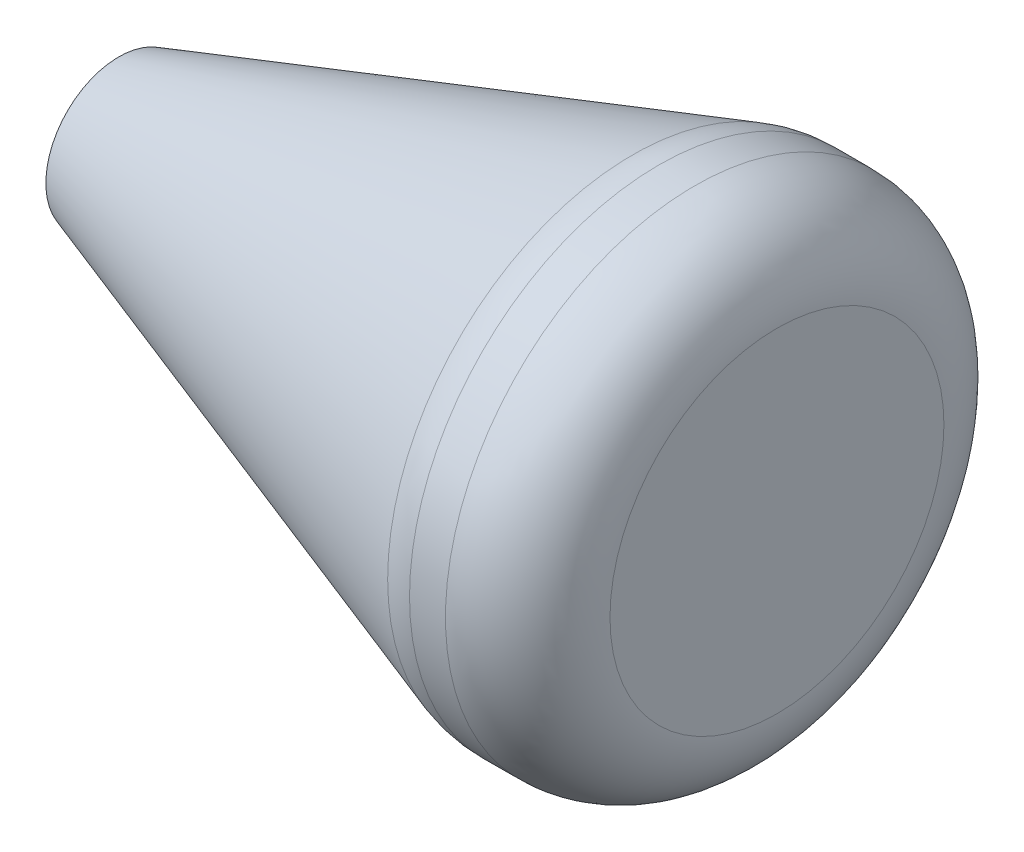
SolidWorks part; units mm, degrees
ref_plane "Front Plane" through (0, 0, 0) normal (1, 0, 0) x (0, 1, 0)
ref_plane "Top Plane" through (0, 0, 0) normal (0, 0, 1) x (0, 1, 0)
ref_plane "Right Plane" through (0, 0, 0) normal (0, 1, 0) x (-1, 0, 0)
sketch "Sketch1" plane through (0, 0, 0) normal (0, 0, 1) x (0, 1, 0)
  line L0 (0, 0) -> (0, 6)
  line L1 (2.8, 40) -> (4.4379, 40)
  line L2 (4.4379, 40) -> (15.1491, 8)
  line L3 (15.1491, 8) -> (15.1491, 0)
  line L4 (15.1491, 0) -> (0, 0)
  line L5 (0, 6) -> (2.8, 6)
  line L6 (2.8, 6) -> (2.8, 40)
  dimension "D1" = 2.8
  dimension "D2" = 34
  dimension "D4" = 8
revolve "Revolve1" add sketch "Sketch1" angle 360 about L0
fillet "Fillet1" radius 5 1 edges at (-8, 0, -15.1491)
fillet "Fillet2" radius 5 1 edges at (0, 0, -15.1491)
